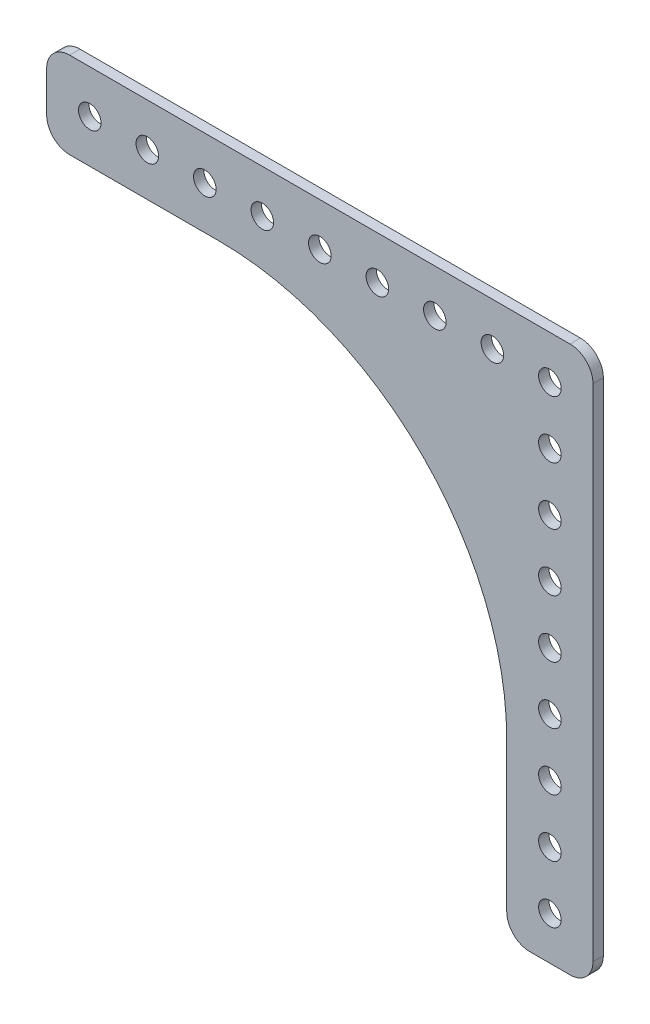
SolidWorks part; units mm, degrees
ref_plane "Front Plane" through (0, 0, 0) normal (0, 0, 1) x (1, 0, 0)
ref_plane "Top Plane" through (0, 0, 0) normal (0, 1, 0) x (1, 0, 0)
ref_plane "Right Plane" through (0, 0, 0) normal (1, 0, 0) x (0, 0, -1)
sketch "Sketch1" plane through (0, 0, 0) normal (0, 0, 1) x (1, 0, 0)
  line L0 (459.7495, 373.6573) -> (426.7295, 373.6573)
  line L1 (523.2495, 373.6573) -> (-137.1505, 373.6573) construction
  line L2 (421.6495, 378.7373) -> (421.6495, 387.6273)
  line L3 (542.2995, 392.7073) -> (-156.2005, 392.7073) construction
  line L4 (426.7295, 392.7073) -> (537.2195, 392.7073)
  line L5 (542.2995, 387.6273) -> (542.2995, 277.1373)
  line L6 (542.2995, 18.0573) -> (542.2995, 392.7073) construction
  line L7 (537.2195, 272.0573) -> (528.3295, 272.0573)
  line L8 (523.2495, 277.1373) -> (523.2495, 310.1573)
  line L9 (523.2495, 18.0573) -> (523.2495, 373.6573) construction
  arc A0 (459.7495, 373.6573) -> (523.2495, 310.1573) centre (459.7495, 310.1573) cw
  arc A1 (528.3295, 272.0573) -> (523.2495, 277.1373) centre (528.3295, 277.1373) cw
  arc A2 (542.2995, 277.1373) -> (537.2195, 272.0573) centre (537.2195, 277.1373) cw
  arc A3 (537.2195, 392.7073) -> (542.2995, 387.6273) centre (537.2195, 387.6273) cw
  arc A4 (421.6495, 387.6273) -> (426.7295, 392.7073) centre (426.7295, 387.6273) cw
  arc A5 (426.7295, 373.6573) -> (421.6495, 378.7373) centre (426.7295, 378.7373) cw
  circle A6 centre (431.1745, 383.1823) radius 2.4892
  circle A7 centre (443.8745, 383.1823) radius 2.4892
  circle A8 centre (456.5745, 383.1823) radius 2.4892
  circle A9 centre (469.2745, 383.1823) radius 2.4892
  circle A10 centre (481.9745, 383.1823) radius 2.4892
  circle A11 centre (494.6745, 383.1823) radius 2.4892
  circle A12 centre (507.3745, 383.1823) radius 2.4892
  circle A13 centre (520.0745, 383.1823) radius 2.4892
  circle A14 centre (532.7745, 383.1823) radius 2.4892
  circle A15 centre (532.7745, 370.4823) radius 2.4892
  circle A16 centre (532.7745, 357.7823) radius 2.4892
  circle A17 centre (532.7745, 345.0823) radius 2.4892
  circle A18 centre (532.7745, 332.3823) radius 2.4892
  circle A19 centre (532.7745, 319.6823) radius 2.4892
  circle A20 centre (532.7745, 306.9823) radius 2.4892
  circle A21 centre (532.7745, 294.2823) radius 2.4892
  circle A22 centre (532.7745, 281.5823) radius 2.4892
  point P23 (523.2495, 373.6573)
  point P28 (542.2995, 272.0573)
  point P31 (542.2995, 392.7073)
  point P34 (421.6495, 392.7073)
  point P37 (421.6495, 373.6573)
  dimension "D3" = 63.5
  dimension "D4" = 5.08
  dimension "D5" = 4.9784
  dimension "D6" = 9.525
  dimension "D7" = 9.525
  dimension "D10" = 12.7
  dimension "D1" = 120.65
  dimension "D2" = 120.65
  dimension "D11" = 9.525
  dimension "D8" = 9
  dimension "D9" = 9
extrude "Boss-Extrude1" add sketch "Sketch1" along normal blind 2.286
